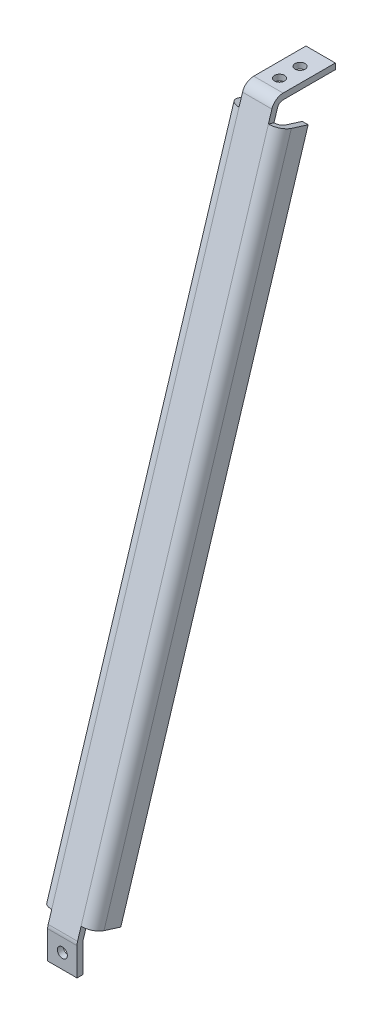
SolidWorks part; units mm, degrees
other "Roof Support Arm 3 Right"
ref_plane "Front Plane" through (0, 0, 0) normal (0, 0, 1) x (1, 0, 0)
ref_plane "Top Plane" through (0, 0, 0) normal (0, 1, 0) x (1, 0, 0)
ref_plane "Right Plane" through (0, 0, 0) normal (1, 0, 0) x (0, 0, -1)
sketch3d "Formed Web Section Sketch datum points"
  point P0 (185, 0, 0)
  point P1 (185, 10, 0)
  point P2 (185, 0, 10)
ref_plane "Formed Web Section Sketch plane" through (185, 0, 0) normal (1, 0, 0) x (0, 0, -1)
sketch "Formed Web Section Sketch" plane through (185, 0, 0) normal (1, 0, 0) x (0, 0, -1)
  line L0 (-22, -64) -> (-39.7926, -64)
  line L1 (-43.6115, -66.8099) -> (-109.8189, -279.2665)
  line L2 (-110, -280.4566) -> (-110, -290)
  line L3 (-110, -290) -> (-108, -290)
  line L4 (-108, -290) -> (-108, -280.4566)
  line L5 (-107.9094, -279.8616) -> (-41.702, -67.405)
  line L6 (-39.7926, -66) -> (-22, -66)
  line L7 (-22, -66) -> (-22, -64)
  arc A0 (-39.7926, -64) -> (-43.6115, -66.8099) centre (-39.7926, -68) ccw
  arc A1 (-109.8189, -279.2665) -> (-110, -280.4566) centre (-106, -280.4566) ccw
  arc A2 (-107.9094, -279.8616) -> (-108, -280.4566) centre (-106, -280.4566) ccw
  arc A3 (-39.7926, -66) -> (-41.702, -67.405) centre (-39.7926, -68) ccw
extrude "Formed Web" add sketch "Formed Web Section Sketch" along normal blind 10 separate body
sketch3d "Edge Lip Sketch datum points"
  point P0 (190, -70.9263, 43.8468)
  point P1 (200, -70.9263, 43.8468)
  point P2 (190, -67.9512, 53.394)
ref_plane "Edge Lip Sketch plane" through (0, -77.1026, 24.0273) normal (0, -0.9547, 0.2975) x (-1, 0, 0)
sketch "Edge Lip Sketch" plane through (0, -77.1026, 24.0273) normal (0, -0.9547, 0.2975) x (-1, 0, 0)
  line L0 (-181, -17.7595) -> (-181, -11.7595)
  line L1 (-181, -11.7595) -> (-183, -11.7595)
  line L2 (-183, -11.7595) -> (-183, -17.7595)
  line L3 (-185, -19.7595) -> (-185.1, -19.7595)
  line L4 (-185.1, -19.7595) -> (-185.1, -21.7595)
  line L5 (-185.1, -21.7595) -> (-185, -21.7595)
  line L6 (-199, -17.7595) -> (-199, -11.7595)
  line L7 (-199, -11.7595) -> (-197, -11.7595)
  line L8 (-197, -11.7595) -> (-197, -17.7595)
  line L9 (-195, -19.7595) -> (-194.9, -19.7595)
  line L10 (-194.9, -19.7595) -> (-194.9, -21.7595)
  line L11 (-194.9, -21.7595) -> (-195, -21.7595)
  arc A0 (-185, -21.7595) -> (-181, -17.7595) centre (-185, -17.7595) ccw
  arc A1 (-185, -19.7595) -> (-183, -17.7595) centre (-185, -17.7595) ccw
  arc A2 (-199, -17.7595) -> (-195, -21.7595) centre (-195, -17.7595) ccw
  arc A3 (-197, -17.7595) -> (-195, -19.7595) centre (-195, -17.7595) ccw
extrude "Edge Stiffening Lips" add sketch "Edge Lip Sketch" along normal blind 214.5337
sketch3d "Wall Mount Hole Sketch datum points"
  point P0 (0, -63.8, 0)
  point P1 (10, -63.8, 0)
  point P2 (0, -63.8, 10)
ref_plane "Wall Mount Hole Sketch plane" through (0, -63.8, 0) normal (0, -1, 0) x (-1, 0, 0)
sketch "Wall Mount Hole Sketch" plane through (0, -63.8, 0) normal (0, -1, 0) x (-1, 0, 0)
  circle A0 centre (-190, -29) radius 1.7
  circle A1 centre (-190, -36) radius 1.7
extrude "Wall Mount Holes" cut sketch "Wall Mount Hole Sketch" along normal blind 2.4
sketch3d "Cover Mount Hole Sketch datum points"
  point P0 (0, 0, 107.8)
  point P1 (10, 0, 107.8)
  point P2 (0, 10, 107.8)
ref_plane "Cover Mount Hole Sketch plane" through (0, 0, 107.8) normal (0, 0, 1) x (1, 0, 0)
sketch "Cover Mount Hole Sketch" plane through (0, 0, 107.8) normal (0, 0, 1) x (1, 0, 0)
  circle A0 centre (190, -285) radius 1.7
extrude "Cover Mount Hole" cut sketch "Cover Mount Hole Sketch" along normal blind 2.4
